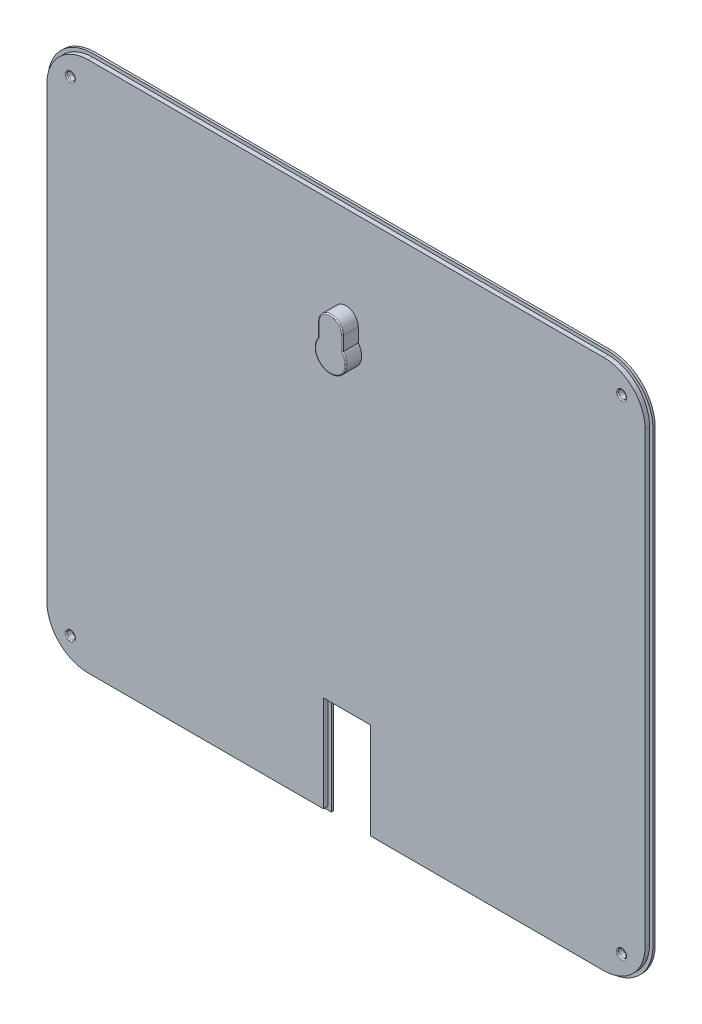
SolidWorks part; units mm, degrees
ref_plane "Front Plane" through (0, 0, 0) normal (0, 0, 1) x (1, 0, 0)
ref_plane "Top Plane" through (0, 0, 0) normal (0, 1, 0) x (1, 0, 0)
ref_plane "Right Plane" through (0, 0, 0) normal (1, 0, 0) x (0, 0, -1)
sketch "Sketch1" plane through (0, 0, 0) normal (0, 0, 1) x (1, 0, 0)
  line L1 (-115, 120) -> (115, 120)
  line L2 (-135, 100) -> (-135, -100)
  line L3 (-115, -120) -> (115, -120)
  line L4 (135, 100) -> (135, -100)
  line L5 (-135, 120) -> (135, -120) construction
  line L6 (-135, -120) -> (135, 120) construction
  arc A0 (-135, -100) -> (-115, -120) centre (-115, -100) ccw
  arc A1 (115, -120) -> (135, -100) centre (115, -100) ccw
  arc A2 (115, 120) -> (135, 100) centre (115, 100) cw
  arc A3 (-115, 120) -> (-135, 100) centre (-115, 100) ccw
  point P0 (0, 0)
  dimension "D3" = 20
  dimension "D1" = 270
  dimension "D2" = 240
extrude "Main Body" add sketch "Sketch1" along normal blind 3
sketch "Sketch2" plane through (0, 0, 3) normal (0, 0, 1) x (1, 0, 0)
  line L0 (9.5, -77.5) -> (9.5, -120.5) construction
  line L1 (-115, 120) -> (115, 120)
  line L2 (-135, 100) -> (-135, -100)
  line L3 (-115, -120) -> (-8.5, -120)
  line L4 (135, 100) -> (135, -100)
  line L5 (115, 120) -> (-115, 120) construction
  line L6 (-135, 100) -> (-135, -100) construction
  line L7 (-8.5, -77.1) -> (9.5, -77.1)
  line L8 (-8.5, -77.1) -> (-8.5, -120)
  line L10 (9.5, -77.1) -> (9.5, -120)
  line L11 (9.5, -120) -> (115, -120)
  arc A0 (-135, -100) -> (-115, -120) centre (-115, -100) ccw
  arc A1 (115, -120) -> (135, -100) centre (115, -100) ccw
  arc A2 (115, 120) -> (135, 100) centre (115, 100) cw
  arc A3 (-115, 120) -> (-135, 100) centre (-115, 100) ccw
  point P0 (0, 0)
  dimension "D3" = 20
  dimension "D1" = 240
  dimension "D2" = 270
  dimension "D4" = 42.9
  dimension "D5" = 18
extrude "Edge Cut" cut sketch "Sketch2" against normal blind 2 thin
sketch "Sketch3" plane through (0, 0, 3) normal (0, 0, 1) x (1, 0, 0)
  line L0 (-115, -120) -> (-8.5, -120) construction
  line L1 (9.5, -120) -> (-8.5, -120)
  line L2 (9.5, -120) -> (9.5, -77)
  line L3 (9.5, -77) -> (-8.5, -77)
  line L4 (-8.5, -120) -> (-8.5, -77)
  dimension "D1" = 18
  dimension "D2" = 43
extrude "Power Cable Cut" cut sketch "Sketch3" against normal blind 3
sketch "Sketch4" plane through (0, 0, 0) normal (0, 0, -1) x (-1, 0, 0)
  line L4 (-115, 120) -> (115, 120) construction
  line L5 (0, 120) -> (0, 0) construction
  line L7 (-3.5, 68.5707) -> (-3.5, 75.5)
  line L9 (3.5, 68.5707) -> (3.5, 75.5)
  arc A2 (-3.5, 68.5707) -> (3.5, 68.5707) centre (0, 65) ccw
  arc A3 (3.5, 75.5) -> (-3.5, 75.5) centre (0, 75.5) ccw
  dimension "D1" = 5
  dimension "D3" = 55
  dimension "D6" = 7
  dimension "D7" = 10.5
extrude "Keyhole Slot" add sketch "Sketch4" against normal blind 8 thin thin type one direction wall 2
sketch "Sketch7" plane through (0, 0, 0) normal (0, 0, -1) x (-1, 0, 0)
  line L0 (0, 126.9212) -> (0, -33.0788) construction
  line L1 (-1.905, 74) -> (1.905, 74)
  line L2 (-1.905, 74) -> (-1.905, 65)
  line L3 (-1.905, 65) -> (1.905, 65)
  line L4 (1.905, 74) -> (1.905, 65)
  line L5 (-115, 120) -> (115, 120) construction
  circle A0 centre (0, 65) radius 5
  circle A1 centre (0, 74) radius 1.905
  dimension "D1" = 10
  dimension "D2" = 3.81
  dimension "D3" = 3.81
  dimension "D4" = 9
  dimension "D5" = 55
extrude "Keyhole" cut sketch "Sketch7" against normal blind 3 contours L1 L4 L3 L2 | A0 | A1
sketch "Sketch8" plane through (0, 0, 8) normal (0, 0, 1) x (1, 0, 0)
  line L2 (5.5, 69.3301) -> (5.5, 75.5)
  line L3 (-5.5, 75.5) -> (-5.5, 69.3301)
  line L4 (5.5, 69.3301) -> (5.5, 75.5)
  line L5 (-5.5, 75.5) -> (-5.5, 69.3301)
  arc A2 (-5.5, 69.3301) -> (5.5, 69.3301) centre (0, 65) ccw
  arc A3 (5.5, 75.5) -> (-5.5, 75.5) centre (0, 75.5) ccw
  arc A4 (-5.5, 69.3301) -> (5.5, 69.3301) centre (0, 65) ccw
  arc A5 (5.5, 75.5) -> (-5.5, 75.5) centre (0, 75.5) ccw
  dimension "D1" = 0
extrude "Keyhole wall" add sketch "Sketch8" along normal blind 2 contours A5 L5 A4 L4
sketch "Sketch9" plane through (0, 0, 0) normal (0, 0, -1) x (-1, 0, 0)
  line L0 (-115, 120) -> (115, 120) construction
  line L1 (-135, -100) -> (-135, 100) construction
  line L2 (-9.5, -120) -> (-115, -120) construction
  line L3 (115, -120) -> (8.5, -120) construction
  line L4 (135, 100) -> (135, -100) construction
  circle A0 centre (-123, 108) radius 1.8
  circle A1 centre (-123, -108) radius 1.8
  circle A2 centre (123, -108) radius 1.8
  circle A3 centre (123, 108) radius 1.8
  dimension "D1" = 3.6
  dimension "D4" = 3.6
  dimension "D7" = 3.6
  dimension "D10" = 3.6
  dimension "D2" = 12
  dimension "D3" = 12
  dimension "D5" = 12
  dimension "D6" = 12
  dimension "D8" = 12
  dimension "D9" = 12
  dimension "D11" = 12
  dimension "D12" = 12
extrude "Screw holes" cut sketch "Sketch9" against normal blind 3
fillet "Fillet1" radius 0.5 16 edges at (-124.8, -108, 0) (-124.8, -108, 3) (121.2, -108, 0) (121.2, -108, 3) (121.2, 108, 0) (121.2, 108, 3) (-124.8, 108, 0) (-124.8, 108, 3) (-5.5, 72.4151, 10) (0, 81, 10) (5.5, 72.4151, 10) (0, 58, 10) (1.905, 71.8114, 0) (-1.905, 71.8114, 0) (0, 75.905, 0) (0, 60, 0)
